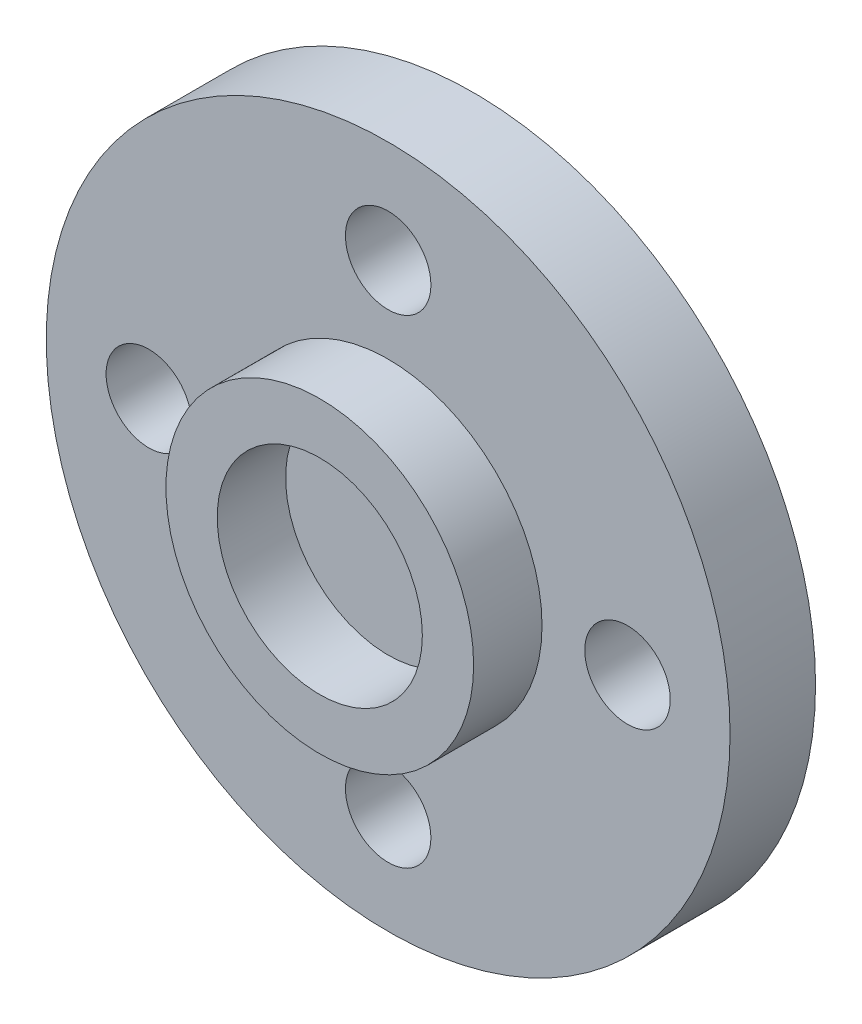
SolidWorks part; units mm, degrees
ref_plane "前视基准面" through (0, 0, 0) normal (0, 0, 1) x (1, 0, 0)
ref_plane "上视基准面" through (0, 0, 0) normal (0, 1, 0) x (1, 0, 0)
ref_plane "右视基准面" through (0, 0, 0) normal (1, 0, 0) x (0, 0, -1)
other "Configuration Table"
sketch "草图1" plane through (0, 0, 0) normal (0, 0, 1) x (1, 0, 0)
  circle A0 centre (0, 0) radius 10
  dimension "D1" = 20
extrude "凸台-拉伸1" add sketch "草图1" along normal blind 2.5
sketch "草图2" plane through (0, 0, 2.5) normal (0, 0, 1) x (1, 0, 0)
  circle A0 centre (0, 0) radius 4.5
  circle A1 centre (0, 0) radius 3
  dimension "D1" = 9
  dimension "D2" = 6
extrude "凸台-拉伸2" add sketch "草图2" along normal blind 2
sketch "草图3" plane through (0, 0, 2.5) normal (0, 0, 1) x (1, 0, 0)
  circle A0 centre (0, 0) radius 7 construction
  circle A1 centre (0, 7) radius 1.25
  circle A2 centre (7, 0) radius 1.25
  circle A3 centre (0, -7) radius 1.25
  circle A4 centre (-7, 0) radius 1.25
  point P14 (0, 0)
  dimension "D1" = 14
  dimension "D2" = 2.5
  dimension "D3" = 4
extrude "切除-拉伸1" cut sketch "草图3" against normal through all
equation "\"q2\"=2.5"
